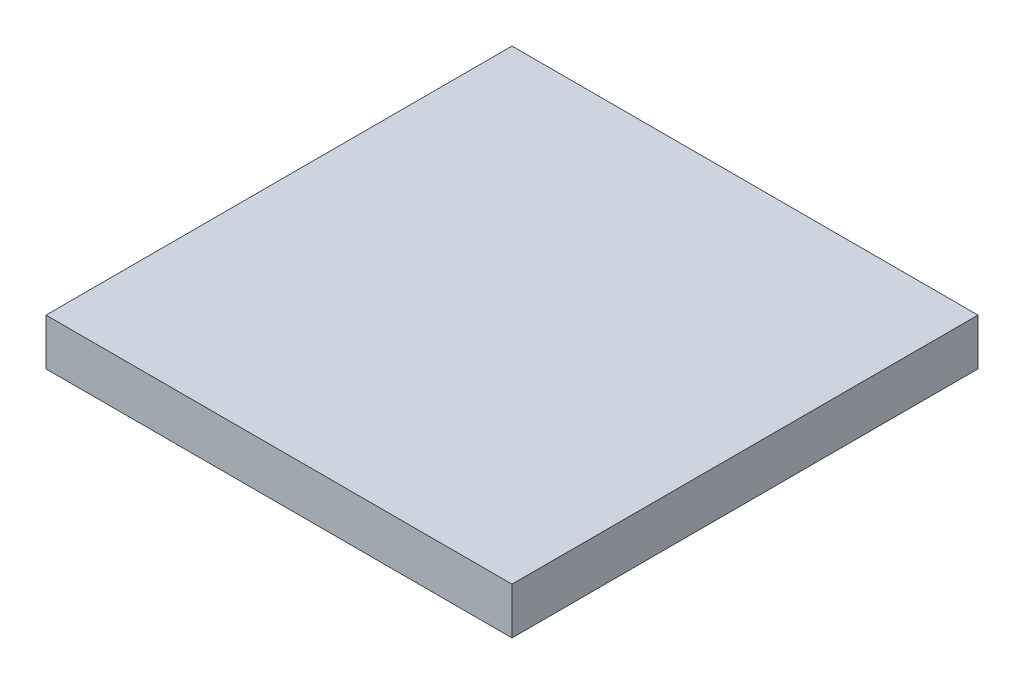
SolidWorks part; units mm, degrees
ref_plane "Front Plane" through (0, 0, 0) normal (0, 0, 1) x (1, 0, 0)
ref_plane "Top Plane" through (0, 0, 0) normal (0, 1, 0) x (1, 0, 0)
ref_plane "Right Plane" through (0, 0, 0) normal (1, 0, 0) x (0, 0, -1)
sketch "Sketch1" plane through (0, 0, 0) normal (0, 1, 0) x (1, 0, 0)
  line L1 (-21, -21) -> (21, -21)
  line L2 (-21, -21) -> (-21, 21)
  line L3 (-21, 21) -> (21, 21)
  line L4 (21, -21) -> (21, 21)
  line L5 (-21, -21) -> (21, 21) construction
  line L6 (-21, 21) -> (21, -21) construction
  point P0 (0, 0)
  dimension "D1" = 42
  dimension "D2" = 42
extrude "Boss-Extrude1" add sketch "Sketch1" along normal blind 4.2
